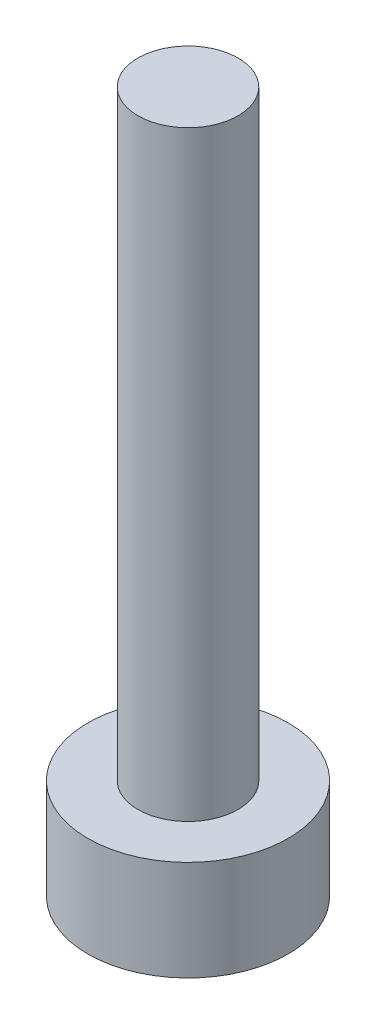
SolidWorks part; units mm, degrees
ref_plane "前视基准面" through (0, 0, 0) normal (0, 0, 1) x (1, 0, 0)
ref_plane "上视基准面" through (0, 0, 0) normal (0, 1, 0) x (1, 0, 0)
ref_plane "右视基准面" through (0, 0, 0) normal (1, 0, 0) x (0, 0, -1)
other "Configuration Table"
sketch "草图1" plane through (0, 0, 0) normal (0, 1, 0) x (1, 0, 0)
  circle A0 centre (0, 0) radius 5
  dimension "D1" = 10
extrude "凸台-拉伸1" add sketch "草图1" along normal blind 5
sketch "草图2" plane through (0, 5, 0) normal (0, 1, 0) x (1, 0, 0)
  circle A0 centre (0, 0) radius 2.5
  dimension "D1" = 5
extrude "凸台-拉伸2" add sketch "草图2" along normal blind 30
cosmetic thread "装饰螺纹线1" parameters "D1"=5, "D2"=4
sketch "草图3" plane through (0, 0, 0) normal (0, -1, 0) x (1, 0, 0)
  line L0 (0, 0) -> (0, 1.4835) construction
  line L1 (-1.0371, 4.1077) -> (1.0371, 4.1077)
  line L2 (-1.0371, 4.1077) -> (-1.0371, -4.1257)
  line L3 (-1.0371, -4.1257) -> (1.0371, -4.1257)
  line L4 (1.0371, 4.1077) -> (1.0371, -4.1257)
extrude "切除-拉伸1" cut sketch "草图3" against normal blind 2
